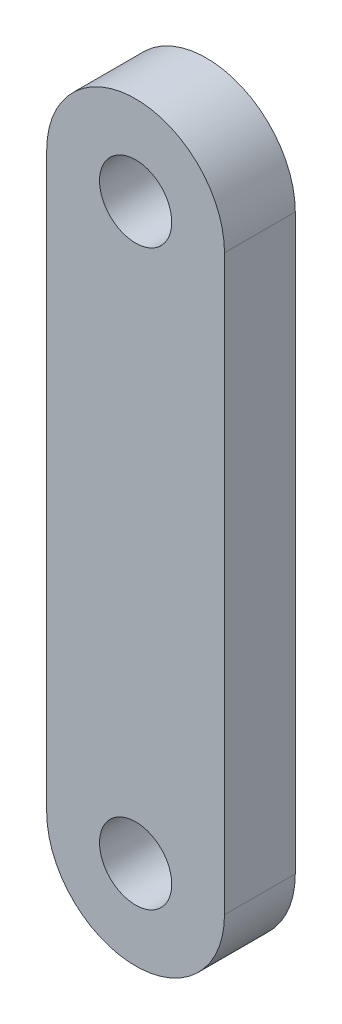
SolidWorks part; units mm, degrees
ref_plane "Front Plane" through (0, 0, 0) normal (0, 0, 1) x (1, 0, 0)
ref_plane "Top Plane" through (0, 0, 0) normal (0, 1, 0) x (1, 0, 0)
ref_plane "Right Plane" through (0, 0, 0) normal (1, 0, 0) x (0, 0, -1)
sketch "Sketch1" plane through (0, 0, 0) normal (0, 0, 1) x (1, 0, 0)
  line L0 (0, 38.075) -> (0, -13.36) construction
  line L1 (7.9756, 38.075) -> (7.9756, -13.36)
  line L2 (-7.9756, 38.075) -> (-7.9756, -13.36)
  arc A0 (7.9756, 38.075) -> (-7.9756, 38.075) centre (0, 38.075) ccw
  arc A1 (-7.9756, -13.36) -> (7.9756, -13.36) centre (0, -13.36) ccw
  circle A2 centre (0, 38.075) radius 3.2385
  circle A3 centre (0, -13.36) radius 3.2385
  point P3 (0, 12.3575)
  dimension "D1" = 6.477
  dimension "D2" = 6.477
  dimension "D3" = 51.435
  dimension "D4" = 15.9512
extrude "Boss-Extrude1" add sketch "Sketch1" along normal blind 6.35
